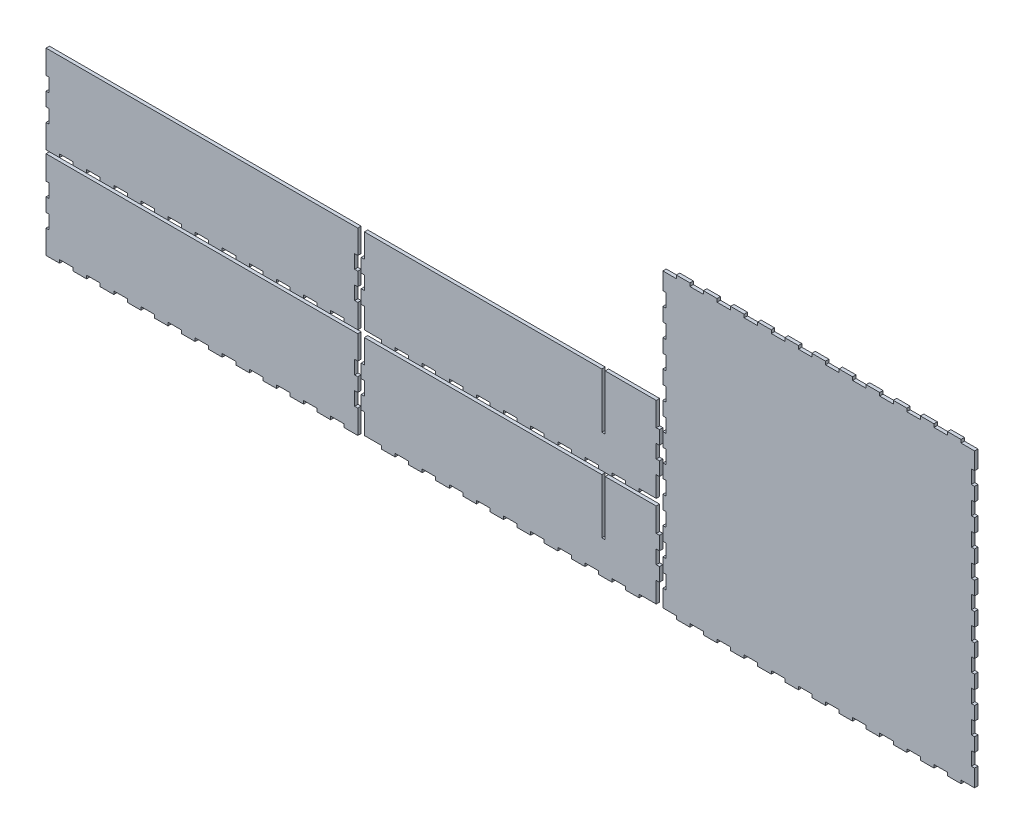
SolidWorks part; units mm, degrees
ref_plane "Front Plane" through (0, 0, 0) normal (0, 0, 1) x (1, 0, 0)
ref_plane "Top Plane" through (0, 0, 0) normal (0, 1, 0) x (1, 0, 0)
ref_plane "Right Plane" through (0, 0, 0) normal (1, 0, 0) x (0, 0, -1)
sketch "Model" plane through (0, 0, 0) normal (0, 0, 1) x (1, 0, 0)
  line L0 (0, 85.725) -> (0, 63.5)
  line L1 (0, 63.5) -> (2.9972, 63.5)
  line L2 (2.9972, 63.5) -> (2.9972, 50.8)
  line L3 (2.9972, 50.8) -> (0, 50.8)
  line L4 (0, 50.8) -> (0, 38.1)
  line L5 (0, 38.1) -> (2.9972, 38.1)
  line L6 (2.9972, 38.1) -> (2.9972, 25.4)
  line L7 (2.9972, 25.4) -> (0, 25.4)
  line L8 (0, 25.4) -> (0, 3.175)
  line L9 (0, 3.175) -> (12.7, 3.175)
  line L10 (12.7, 3.175) -> (12.7, 6.1722)
  line L11 (12.7, 6.1722) -> (25.4, 6.1722)
  line L12 (25.4, 6.1722) -> (25.4, 3.175)
  line L13 (25.4, 3.175) -> (38.1, 3.175)
  line L14 (38.1, 3.175) -> (38.1, 6.1722)
  line L15 (38.1, 6.1722) -> (50.8, 6.1722)
  line L16 (50.8, 6.1722) -> (50.8, 3.175)
  line L17 (50.8, 3.175) -> (63.5, 3.175)
  line L18 (63.5, 3.175) -> (63.5, 6.1722)
  line L19 (63.5, 6.1722) -> (76.2, 6.1722)
  line L20 (76.2, 6.1722) -> (76.2, 3.175)
  line L21 (76.2, 3.175) -> (88.9, 3.175)
  line L22 (88.9, 3.175) -> (88.9, 6.1722)
  line L23 (88.9, 6.1722) -> (101.6, 6.1722)
  line L24 (101.6, 6.1722) -> (101.6, 3.175)
  line L25 (101.6, 3.175) -> (114.3, 3.175)
  line L26 (114.3, 3.175) -> (114.3, 6.1722)
  line L27 (114.3, 6.1722) -> (127, 6.1722)
  line L28 (127, 6.1722) -> (127, 3.175)
  line L29 (127, 3.175) -> (139.7, 3.175)
  line L30 (139.7, 3.175) -> (139.7, 6.1722)
  line L31 (139.7, 6.1722) -> (152.4, 6.1722)
  line L32 (152.4, 6.1722) -> (152.4, 3.175)
  line L33 (152.4, 3.175) -> (165.1, 3.175)
  line L34 (165.1, 3.175) -> (165.1, 6.1722)
  line L35 (165.1, 6.1722) -> (177.8, 6.1722)
  line L36 (177.8, 6.1722) -> (177.8, 3.175)
  line L37 (177.8, 3.175) -> (190.5, 3.175)
  line L38 (190.5, 3.175) -> (190.5, 6.1722)
  line L39 (190.5, 6.1722) -> (203.2, 6.1722)
  line L40 (203.2, 6.1722) -> (203.2, 3.175)
  line L41 (203.2, 3.175) -> (215.9, 3.175)
  line L42 (215.9, 3.175) -> (215.9, 6.1722)
  line L43 (215.9, 6.1722) -> (228.6, 6.1722)
  line L44 (228.6, 6.1722) -> (228.6, 3.175)
  line L45 (228.6, 3.175) -> (241.3, 3.175)
  line L46 (241.3, 3.175) -> (241.3, 6.1722)
  line L47 (241.3, 6.1722) -> (254, 6.1722)
  line L48 (254, 6.1722) -> (254, 3.175)
  line L49 (254, 3.175) -> (266.7, 3.175)
  line L50 (266.7, 3.175) -> (266.7, 6.1722)
  line L51 (266.7, 6.1722) -> (279.4, 6.1722)
  line L52 (279.4, 6.1722) -> (279.4, 3.175)
  line L53 (279.4, 3.175) -> (292.1, 3.175)
  line L54 (292.1, 3.175) -> (292.1, 25.4)
  line L55 (292.1, 25.4) -> (289.1028, 25.4)
  line L56 (289.1028, 25.4) -> (289.1028, 38.1)
  line L57 (289.1028, 38.1) -> (292.1, 38.1)
  line L58 (292.1, 38.1) -> (292.1, 50.8)
  line L59 (292.1, 50.8) -> (289.1028, 50.8)
  line L60 (289.1028, 50.8) -> (289.1028, 63.5)
  line L61 (289.1028, 63.5) -> (292.1, 63.5)
  line L62 (292.1, 63.5) -> (292.1, 85.725)
  line L63 (292.1, 85.725) -> (0, 85.725)
  line L64 (298.2722, 85.725) -> (298.2722, 63.5)
  line L65 (298.2722, 63.5) -> (295.275, 63.5)
  line L66 (295.275, 63.5) -> (295.275, 50.8)
  line L67 (295.275, 50.8) -> (298.2722, 50.8)
  line L68 (298.2722, 50.8) -> (298.2722, 38.1)
  line L69 (298.2722, 38.1) -> (295.275, 38.1)
  line L70 (295.275, 38.1) -> (295.275, 25.4)
  line L71 (295.275, 25.4) -> (298.2722, 25.4)
  line L72 (298.2722, 25.4) -> (298.2722, 6.1722)
  line L73 (298.2722, 6.1722) -> (314.325, 6.1722)
  line L74 (314.325, 6.1722) -> (314.325, 3.175)
  line L75 (314.325, 3.175) -> (327.025, 3.175)
  line L76 (327.025, 3.175) -> (327.025, 6.1722)
  line L77 (327.025, 6.1722) -> (339.725, 6.1722)
  line L78 (339.725, 6.1722) -> (339.725, 3.175)
  line L79 (339.725, 3.175) -> (352.425, 3.175)
  line L80 (352.425, 3.175) -> (352.425, 6.1722)
  line L81 (352.425, 6.1722) -> (365.125, 6.1722)
  line L82 (365.125, 6.1722) -> (365.125, 3.175)
  line L83 (365.125, 3.175) -> (377.825, 3.175)
  line L84 (377.825, 3.175) -> (377.825, 6.1722)
  line L85 (377.825, 6.1722) -> (390.525, 6.1722)
  line L86 (390.525, 6.1722) -> (390.525, 3.175)
  line L87 (390.525, 3.175) -> (403.225, 3.175)
  line L88 (403.225, 3.175) -> (403.225, 6.1722)
  line L89 (403.225, 6.1722) -> (415.925, 6.1722)
  line L90 (415.925, 6.1722) -> (415.925, 3.175)
  line L91 (415.925, 3.175) -> (428.625, 3.175)
  line L92 (428.625, 3.175) -> (428.625, 6.1722)
  line L93 (428.625, 6.1722) -> (441.325, 6.1722)
  line L94 (441.325, 6.1722) -> (441.325, 3.175)
  line L95 (441.325, 3.175) -> (454.025, 3.175)
  line L96 (454.025, 3.175) -> (454.025, 6.1722)
  line L97 (454.025, 6.1722) -> (466.725, 6.1722)
  line L98 (466.725, 6.1722) -> (466.725, 3.175)
  line L99 (466.725, 3.175) -> (479.425, 3.175)
  line L100 (479.425, 3.175) -> (479.425, 6.1722)
  line L101 (479.425, 6.1722) -> (492.125, 6.1722)
  line L102 (492.125, 6.1722) -> (492.125, 3.175)
  line L103 (492.125, 3.175) -> (504.825, 3.175)
  line L104 (504.825, 3.175) -> (504.825, 6.1722)
  line L105 (504.825, 6.1722) -> (517.525, 6.1722)
  line L106 (517.525, 6.1722) -> (517.525, 3.175)
  line L107 (517.525, 3.175) -> (530.225, 3.175)
  line L108 (530.225, 3.175) -> (530.225, 6.1722)
  line L109 (530.225, 6.1722) -> (542.925, 6.1722)
  line L110 (542.925, 6.1722) -> (542.925, 3.175)
  line L111 (542.925, 3.175) -> (555.625, 3.175)
  line L112 (555.625, 3.175) -> (555.625, 6.1722)
  line L113 (555.625, 6.1722) -> (571.6778, 6.1722)
  line L114 (571.6778, 6.1722) -> (571.6778, 25.4)
  line L115 (571.6778, 25.4) -> (574.675, 25.4)
  line L116 (574.675, 25.4) -> (574.675, 38.1)
  line L117 (574.675, 38.1) -> (571.6778, 38.1)
  line L118 (571.6778, 38.1) -> (571.6778, 50.8)
  line L119 (571.6778, 50.8) -> (574.675, 50.8)
  line L120 (574.675, 50.8) -> (574.675, 63.5)
  line L121 (574.675, 63.5) -> (571.6778, 63.5)
  line L122 (571.6778, 63.5) -> (571.6778, 85.725)
  line L123 (571.6778, 85.725) -> (298.2722, 85.725)
  line L124 (857.25, 3.175) -> (857.25, 6.1722)
  line L125 (857.25, 6.1722) -> (869.95, 6.1722)
  line L126 (869.95, 6.1722) -> (869.95, 22.225)
  line L127 (869.95, 22.225) -> (866.9528, 22.225)
  line L128 (866.9528, 22.225) -> (866.9528, 34.925)
  line L129 (866.9528, 34.925) -> (869.95, 34.925)
  line L130 (869.95, 34.925) -> (869.95, 47.625)
  line L131 (869.95, 47.625) -> (866.9528, 47.625)
  line L132 (866.9528, 47.625) -> (866.9528, 60.325)
  line L133 (866.9528, 60.325) -> (869.95, 60.325)
  line L134 (869.95, 60.325) -> (869.95, 73.025)
  line L135 (869.95, 73.025) -> (866.9528, 73.025)
  line L136 (866.9528, 73.025) -> (866.9528, 85.725)
  line L137 (866.9528, 85.725) -> (869.95, 85.725)
  line L138 (869.95, 85.725) -> (869.95, 98.425)
  line L139 (869.95, 98.425) -> (866.9528, 98.425)
  line L140 (866.9528, 98.425) -> (866.9528, 111.125)
  line L141 (866.9528, 111.125) -> (869.95, 111.125)
  line L142 (869.95, 111.125) -> (869.95, 123.825)
  line L143 (869.95, 123.825) -> (866.9528, 123.825)
  line L144 (866.9528, 123.825) -> (866.9528, 136.525)
  line L145 (866.9528, 136.525) -> (869.95, 136.525)
  line L146 (869.95, 136.525) -> (869.95, 149.225)
  line L147 (869.95, 149.225) -> (866.9528, 149.225)
  line L148 (866.9528, 149.225) -> (866.9528, 161.925)
  line L149 (866.9528, 161.925) -> (869.95, 161.925)
  line L150 (869.95, 161.925) -> (869.95, 174.625)
  line L151 (869.95, 174.625) -> (866.9528, 174.625)
  line L152 (866.9528, 174.625) -> (866.9528, 187.325)
  line L153 (866.9528, 187.325) -> (869.95, 187.325)
  line L154 (869.95, 187.325) -> (869.95, 200.025)
  line L155 (869.95, 200.025) -> (866.9528, 200.025)
  line L156 (866.9528, 200.025) -> (866.9528, 212.725)
  line L157 (866.9528, 212.725) -> (869.95, 212.725)
  line L158 (869.95, 212.725) -> (869.95, 225.425)
  line L159 (869.95, 225.425) -> (866.9528, 225.425)
  line L160 (866.9528, 225.425) -> (866.9528, 238.125)
  line L161 (866.9528, 238.125) -> (869.95, 238.125)
  line L162 (869.95, 238.125) -> (869.95, 250.825)
  line L163 (869.95, 250.825) -> (866.9528, 250.825)
  line L164 (866.9528, 250.825) -> (866.9528, 263.525)
  line L165 (866.9528, 263.525) -> (869.95, 263.525)
  line L166 (869.95, 263.525) -> (869.95, 279.5778)
  line L167 (869.95, 279.5778) -> (857.25, 279.5778)
  line L168 (857.25, 279.5778) -> (857.25, 282.575)
  line L169 (857.25, 282.575) -> (844.55, 282.575)
  line L170 (844.55, 282.575) -> (844.55, 279.5778)
  line L171 (844.55, 279.5778) -> (831.85, 279.5778)
  line L172 (831.85, 279.5778) -> (831.85, 282.575)
  line L173 (831.85, 282.575) -> (819.15, 282.575)
  line L174 (819.15, 282.575) -> (819.15, 279.5778)
  line L175 (819.15, 279.5778) -> (806.45, 279.5778)
  line L176 (806.45, 279.5778) -> (806.45, 282.575)
  line L177 (806.45, 282.575) -> (793.75, 282.575)
  line L178 (793.75, 282.575) -> (793.75, 279.5778)
  line L179 (793.75, 279.5778) -> (781.05, 279.5778)
  line L180 (781.05, 279.5778) -> (781.05, 282.575)
  line L181 (781.05, 282.575) -> (768.35, 282.575)
  line L182 (768.35, 282.575) -> (768.35, 279.5778)
  line L183 (768.35, 279.5778) -> (755.65, 279.5778)
  line L184 (755.65, 279.5778) -> (755.65, 282.575)
  line L185 (755.65, 282.575) -> (742.95, 282.575)
  line L186 (742.95, 282.575) -> (742.95, 279.5778)
  line L187 (742.95, 279.5778) -> (730.25, 279.5778)
  line L188 (730.25, 279.5778) -> (730.25, 282.575)
  line L189 (730.25, 282.575) -> (717.55, 282.575)
  line L190 (717.55, 282.575) -> (717.55, 279.5778)
  line L191 (717.55, 279.5778) -> (704.85, 279.5778)
  line L192 (704.85, 279.5778) -> (704.85, 282.575)
  line L193 (704.85, 282.575) -> (692.15, 282.575)
  line L194 (692.15, 282.575) -> (692.15, 279.5778)
  line L195 (692.15, 279.5778) -> (679.45, 279.5778)
  line L196 (679.45, 279.5778) -> (679.45, 282.575)
  line L197 (679.45, 282.575) -> (666.75, 282.575)
  line L198 (666.75, 282.575) -> (666.75, 279.5778)
  line L199 (666.75, 279.5778) -> (654.05, 279.5778)
  line L200 (654.05, 279.5778) -> (654.05, 282.575)
  line L201 (654.05, 282.575) -> (641.35, 282.575)
  line L202 (641.35, 282.575) -> (641.35, 279.5778)
  line L203 (641.35, 279.5778) -> (628.65, 279.5778)
  line L204 (628.65, 279.5778) -> (628.65, 282.575)
  line L205 (628.65, 282.575) -> (615.95, 282.575)
  line L206 (615.95, 282.575) -> (615.95, 279.5778)
  line L207 (615.95, 279.5778) -> (603.25, 279.5778)
  line L208 (603.25, 279.5778) -> (603.25, 282.575)
  line L209 (603.25, 282.575) -> (590.55, 282.575)
  line L210 (590.55, 282.575) -> (590.55, 279.5778)
  line L211 (590.55, 279.5778) -> (577.85, 279.5778)
  line L212 (577.85, 279.5778) -> (577.85, 263.525)
  line L213 (577.85, 263.525) -> (580.8472, 263.525)
  line L214 (580.8472, 263.525) -> (580.8472, 250.825)
  line L215 (580.8472, 250.825) -> (577.85, 250.825)
  line L216 (577.85, 250.825) -> (577.85, 238.125)
  line L217 (577.85, 238.125) -> (580.8472, 238.125)
  line L218 (580.8472, 238.125) -> (580.8472, 225.425)
  line L219 (580.8472, 225.425) -> (577.85, 225.425)
  line L220 (577.85, 225.425) -> (577.85, 212.725)
  line L221 (577.85, 212.725) -> (580.8472, 212.725)
  line L222 (580.8472, 212.725) -> (580.8472, 200.025)
  line L223 (580.8472, 200.025) -> (577.85, 200.025)
  line L224 (577.85, 200.025) -> (577.85, 187.325)
  line L225 (577.85, 187.325) -> (580.8472, 187.325)
  line L226 (580.8472, 187.325) -> (580.8472, 174.625)
  line L227 (580.8472, 174.625) -> (577.85, 174.625)
  line L228 (577.85, 174.625) -> (577.85, 161.925)
  line L229 (577.85, 161.925) -> (580.8472, 161.925)
  line L230 (580.8472, 161.925) -> (580.8472, 149.225)
  line L231 (580.8472, 149.225) -> (577.85, 149.225)
  line L232 (577.85, 149.225) -> (577.85, 136.525)
  line L233 (577.85, 136.525) -> (580.8472, 136.525)
  line L234 (580.8472, 136.525) -> (580.8472, 123.825)
  line L235 (580.8472, 123.825) -> (577.85, 123.825)
  line L236 (577.85, 123.825) -> (577.85, 111.125)
  line L237 (577.85, 111.125) -> (580.8472, 111.125)
  line L238 (580.8472, 111.125) -> (580.8472, 98.425)
  line L239 (580.8472, 98.425) -> (577.85, 98.425)
  line L240 (577.85, 98.425) -> (577.85, 85.725)
  line L241 (577.85, 85.725) -> (580.8472, 85.725)
  line L242 (580.8472, 85.725) -> (580.8472, 73.025)
  line L243 (580.8472, 73.025) -> (577.85, 73.025)
  line L244 (577.85, 73.025) -> (577.85, 60.325)
  line L245 (577.85, 60.325) -> (580.8472, 60.325)
  line L246 (580.8472, 60.325) -> (580.8472, 47.625)
  line L247 (580.8472, 47.625) -> (577.85, 47.625)
  line L248 (577.85, 47.625) -> (577.85, 34.925)
  line L249 (577.85, 34.925) -> (580.8472, 34.925)
  line L250 (580.8472, 34.925) -> (580.8472, 22.225)
  line L251 (580.8472, 22.225) -> (577.85, 22.225)
  line L252 (577.85, 22.225) -> (577.85, 6.1722)
  line L253 (577.85, 6.1722) -> (590.55, 6.1722)
  line L254 (590.55, 6.1722) -> (590.55, 3.175)
  line L255 (590.55, 3.175) -> (603.25, 3.175)
  line L256 (603.25, 3.175) -> (603.25, 6.1722)
  line L257 (603.25, 6.1722) -> (615.95, 6.1722)
  line L258 (615.95, 6.1722) -> (615.95, 3.175)
  line L259 (615.95, 3.175) -> (628.65, 3.175)
  line L260 (628.65, 3.175) -> (628.65, 6.1722)
  line L261 (628.65, 6.1722) -> (641.35, 6.1722)
  line L262 (641.35, 6.1722) -> (641.35, 3.175)
  line L263 (641.35, 3.175) -> (654.05, 3.175)
  line L264 (654.05, 3.175) -> (654.05, 6.1722)
  line L265 (654.05, 6.1722) -> (666.75, 6.1722)
  line L266 (666.75, 6.1722) -> (666.75, 3.175)
  line L267 (666.75, 3.175) -> (679.45, 3.175)
  line L268 (679.45, 3.175) -> (679.45, 6.1722)
  line L269 (679.45, 6.1722) -> (692.15, 6.1722)
  line L270 (692.15, 6.1722) -> (692.15, 3.175)
  line L271 (692.15, 3.175) -> (704.85, 3.175)
  line L272 (704.85, 3.175) -> (704.85, 6.1722)
  line L273 (704.85, 6.1722) -> (717.55, 6.1722)
  line L274 (717.55, 6.1722) -> (717.55, 3.175)
  line L275 (717.55, 3.175) -> (730.25, 3.175)
  line L276 (730.25, 3.175) -> (730.25, 6.1722)
  line L277 (730.25, 6.1722) -> (742.95, 6.1722)
  line L278 (742.95, 6.1722) -> (742.95, 3.175)
  line L279 (742.95, 3.175) -> (755.65, 3.175)
  line L280 (755.65, 3.175) -> (755.65, 6.1722)
  line L281 (755.65, 6.1722) -> (768.35, 6.1722)
  line L282 (768.35, 6.1722) -> (768.35, 3.175)
  line L283 (768.35, 3.175) -> (781.05, 3.175)
  line L284 (781.05, 3.175) -> (781.05, 6.1722)
  line L285 (781.05, 6.1722) -> (793.75, 6.1722)
  line L286 (793.75, 6.1722) -> (793.75, 3.175)
  line L287 (793.75, 3.175) -> (806.45, 3.175)
  line L288 (806.45, 3.175) -> (806.45, 6.1722)
  line L289 (806.45, 6.1722) -> (819.15, 6.1722)
  line L290 (819.15, 6.1722) -> (819.15, 3.175)
  line L291 (819.15, 3.175) -> (831.85, 3.175)
  line L292 (831.85, 3.175) -> (831.85, 6.1722)
  line L293 (831.85, 6.1722) -> (844.55, 6.1722)
  line L294 (844.55, 6.1722) -> (844.55, 3.175)
  line L295 (844.55, 3.175) -> (857.25, 3.175)
  line L296 (0, 171.45) -> (0, 149.225)
  line L297 (0, 149.225) -> (2.9972, 149.225)
  line L298 (2.9972, 149.225) -> (2.9972, 136.525)
  line L299 (2.9972, 136.525) -> (0, 136.525)
  line L300 (0, 136.525) -> (0, 123.825)
  line L301 (0, 123.825) -> (2.9972, 123.825)
  line L302 (2.9972, 123.825) -> (2.9972, 111.125)
  line L303 (2.9972, 111.125) -> (0, 111.125)
  line L304 (0, 111.125) -> (0, 88.9)
  line L305 (0, 88.9) -> (12.7, 88.9)
  line L306 (12.7, 88.9) -> (12.7, 91.8972)
  line L307 (12.7, 91.8972) -> (25.4, 91.8972)
  line L308 (25.4, 91.8972) -> (25.4, 88.9)
  line L309 (25.4, 88.9) -> (38.1, 88.9)
  line L310 (38.1, 88.9) -> (38.1, 91.8972)
  line L311 (38.1, 91.8972) -> (50.8, 91.8972)
  line L312 (50.8, 91.8972) -> (50.8, 88.9)
  line L313 (50.8, 88.9) -> (63.5, 88.9)
  line L314 (63.5, 88.9) -> (63.5, 91.8972)
  line L315 (63.5, 91.8972) -> (76.2, 91.8972)
  line L316 (76.2, 91.8972) -> (76.2, 88.9)
  line L317 (76.2, 88.9) -> (88.9, 88.9)
  line L318 (88.9, 88.9) -> (88.9, 91.8972)
  line L319 (88.9, 91.8972) -> (101.6, 91.8972)
  line L320 (101.6, 91.8972) -> (101.6, 88.9)
  line L321 (101.6, 88.9) -> (114.3, 88.9)
  line L322 (114.3, 88.9) -> (114.3, 91.8972)
  line L323 (114.3, 91.8972) -> (127, 91.8972)
  line L324 (127, 91.8972) -> (127, 88.9)
  line L325 (127, 88.9) -> (139.7, 88.9)
  line L326 (139.7, 88.9) -> (139.7, 91.8972)
  line L327 (139.7, 91.8972) -> (152.4, 91.8972)
  line L328 (152.4, 91.8972) -> (152.4, 88.9)
  line L329 (152.4, 88.9) -> (165.1, 88.9)
  line L330 (165.1, 88.9) -> (165.1, 91.8972)
  line L331 (165.1, 91.8972) -> (177.8, 91.8972)
  line L332 (177.8, 91.8972) -> (177.8, 88.9)
  line L333 (177.8, 88.9) -> (190.5, 88.9)
  line L334 (190.5, 88.9) -> (190.5, 91.8972)
  line L335 (190.5, 91.8972) -> (203.2, 91.8972)
  line L336 (203.2, 91.8972) -> (203.2, 88.9)
  line L337 (203.2, 88.9) -> (215.9, 88.9)
  line L338 (215.9, 88.9) -> (215.9, 91.8972)
  line L339 (215.9, 91.8972) -> (228.6, 91.8972)
  line L340 (228.6, 91.8972) -> (228.6, 88.9)
  line L341 (228.6, 88.9) -> (241.3, 88.9)
  line L342 (241.3, 88.9) -> (241.3, 91.8972)
  line L343 (241.3, 91.8972) -> (254, 91.8972)
  line L344 (254, 91.8972) -> (254, 88.9)
  line L345 (254, 88.9) -> (266.7, 88.9)
  line L346 (266.7, 88.9) -> (266.7, 91.8972)
  line L347 (266.7, 91.8972) -> (279.4, 91.8972)
  line L348 (279.4, 91.8972) -> (279.4, 88.9)
  line L349 (279.4, 88.9) -> (292.1, 88.9)
  line L350 (292.1, 88.9) -> (292.1, 111.125)
  line L351 (292.1, 111.125) -> (289.1028, 111.125)
  line L352 (289.1028, 111.125) -> (289.1028, 123.825)
  line L353 (289.1028, 123.825) -> (292.1, 123.825)
  line L354 (292.1, 123.825) -> (292.1, 136.525)
  line L355 (292.1, 136.525) -> (289.1028, 136.525)
  line L356 (289.1028, 136.525) -> (289.1028, 149.225)
  line L357 (289.1028, 149.225) -> (292.1, 149.225)
  line L358 (292.1, 149.225) -> (292.1, 171.45)
  line L359 (292.1, 171.45) -> (0, 171.45)
  line L360 (298.2722, 171.45) -> (298.2722, 149.225)
  line L361 (298.2722, 149.225) -> (295.275, 149.225)
  line L362 (295.275, 149.225) -> (295.275, 136.525)
  line L363 (295.275, 136.525) -> (298.2722, 136.525)
  line L364 (298.2722, 136.525) -> (298.2722, 123.825)
  line L365 (298.2722, 123.825) -> (295.275, 123.825)
  line L366 (295.275, 123.825) -> (295.275, 111.125)
  line L367 (295.275, 111.125) -> (298.2722, 111.125)
  line L368 (298.2722, 111.125) -> (298.2722, 91.8972)
  line L369 (298.2722, 91.8972) -> (314.325, 91.8972)
  line L370 (314.325, 91.8972) -> (314.325, 88.9)
  line L371 (314.325, 88.9) -> (327.025, 88.9)
  line L372 (327.025, 88.9) -> (327.025, 91.8972)
  line L373 (327.025, 91.8972) -> (339.725, 91.8972)
  line L374 (339.725, 91.8972) -> (339.725, 88.9)
  line L375 (339.725, 88.9) -> (352.425, 88.9)
  line L376 (352.425, 88.9) -> (352.425, 91.8972)
  line L377 (352.425, 91.8972) -> (365.125, 91.8972)
  line L378 (365.125, 91.8972) -> (365.125, 88.9)
  line L379 (365.125, 88.9) -> (377.825, 88.9)
  line L380 (377.825, 88.9) -> (377.825, 91.8972)
  line L381 (377.825, 91.8972) -> (390.525, 91.8972)
  line L382 (390.525, 91.8972) -> (390.525, 88.9)
  line L383 (390.525, 88.9) -> (403.225, 88.9)
  line L384 (403.225, 88.9) -> (403.225, 91.8972)
  line L385 (403.225, 91.8972) -> (415.925, 91.8972)
  line L386 (415.925, 91.8972) -> (415.925, 88.9)
  line L387 (415.925, 88.9) -> (428.625, 88.9)
  line L388 (428.625, 88.9) -> (428.625, 91.8972)
  line L389 (428.625, 91.8972) -> (441.325, 91.8972)
  line L390 (441.325, 91.8972) -> (441.325, 88.9)
  line L391 (441.325, 88.9) -> (454.025, 88.9)
  line L392 (454.025, 88.9) -> (454.025, 91.8972)
  line L393 (454.025, 91.8972) -> (466.725, 91.8972)
  line L394 (466.725, 91.8972) -> (466.725, 88.9)
  line L395 (466.725, 88.9) -> (479.425, 88.9)
  line L396 (479.425, 88.9) -> (479.425, 91.8972)
  line L397 (479.425, 91.8972) -> (492.125, 91.8972)
  line L398 (492.125, 91.8972) -> (492.125, 88.9)
  line L399 (492.125, 88.9) -> (504.825, 88.9)
  line L400 (504.825, 88.9) -> (504.825, 91.8972)
  line L401 (504.825, 91.8972) -> (517.525, 91.8972)
  line L402 (517.525, 91.8972) -> (517.525, 88.9)
  line L403 (517.525, 88.9) -> (530.225, 88.9)
  line L404 (530.225, 88.9) -> (530.225, 91.8972)
  line L405 (530.225, 91.8972) -> (542.925, 91.8972)
  line L406 (542.925, 91.8972) -> (542.925, 88.9)
  line L407 (542.925, 88.9) -> (555.625, 88.9)
  line L408 (555.625, 88.9) -> (555.625, 91.8972)
  line L409 (555.625, 91.8972) -> (571.6778, 91.8972)
  line L410 (571.6778, 91.8972) -> (571.6778, 111.125)
  line L411 (571.6778, 111.125) -> (574.675, 111.125)
  line L412 (574.675, 111.125) -> (574.675, 123.825)
  line L413 (574.675, 123.825) -> (571.6778, 123.825)
  line L414 (571.6778, 123.825) -> (571.6778, 136.525)
  line L415 (571.6778, 136.525) -> (574.675, 136.525)
  line L416 (574.675, 136.525) -> (574.675, 149.225)
  line L417 (574.675, 149.225) -> (571.6778, 149.225)
  line L418 (571.6778, 149.225) -> (571.6778, 171.45)
  line L419 (571.6778, 171.45) -> (298.2722, 171.45)
  point P420 (0, 0)
  dimension "D1" = 22.225
extrude "Boss-Extrude1" add sketch "Model" along normal blind 3.175
sketch "Sketch2" plane through (0, 0, 3.175) normal (0, 0, 1) x (1, 0, 0)
  line L0 (571.6778, 171.45) -> (298.2722, 171.45) construction
  line L1 (520.7, 171.45) -> (523.875, 171.45)
  line L2 (520.7, 171.45) -> (520.7, 120.142)
  line L3 (520.7, 120.142) -> (523.875, 120.142)
  line L4 (523.875, 171.45) -> (523.875, 120.142)
  line L10 (574.675, 136.525) -> (574.675, 149.225) construction
  line L12 (574.675, 50.8) -> (574.675, 63.5) construction
  line L13 (571.6778, 85.725) -> (298.2722, 85.725) construction
  line L14 (520.7, 85.725) -> (523.875, 85.725)
  line L15 (520.7, 85.725) -> (520.7, 34.417)
  line L16 (520.7, 34.417) -> (523.875, 34.417)
  line L17 (523.875, 85.725) -> (523.875, 34.417)
  point P14 (574.675, 142.875)
  dimension "D1" = 3.175
  dimension "D2" = 51.308
  dimension "D3" = 50.8
  dimension "D4" = 51.308
  dimension "D5" = 50.8
  dimension "D6" = 3.175
extrude "Cut-Extrude1" cut sketch "Sketch2" against normal up to next (3.175 mm away)
